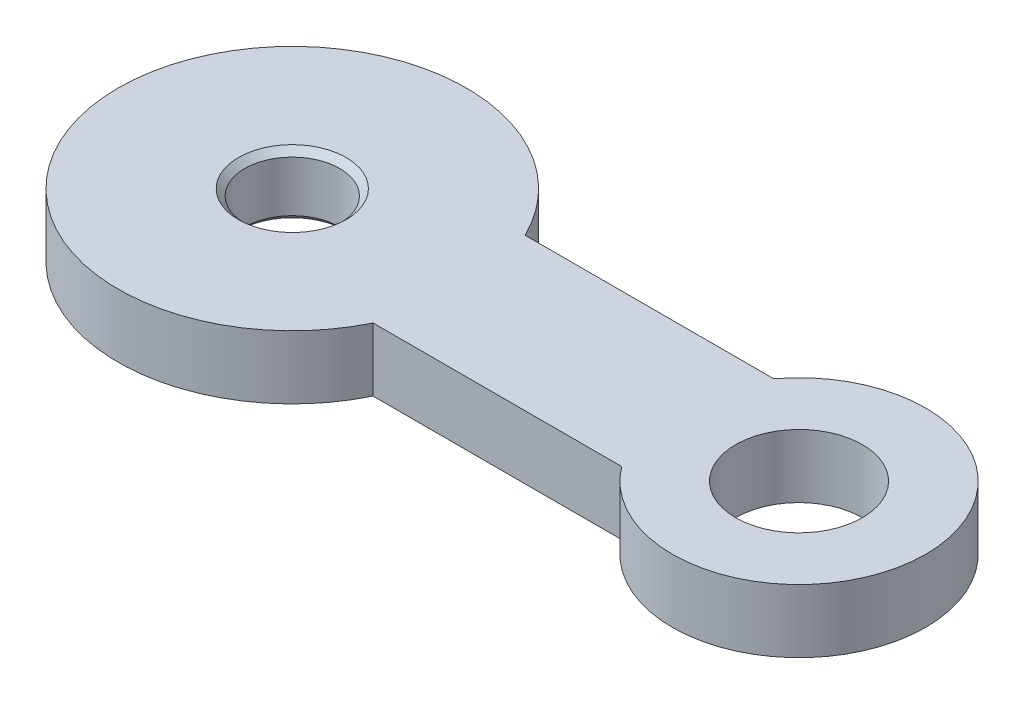
SolidWorks part; units mm, degrees
material "Brass"
ref_plane "Front Plane" through (0, 0, 0) normal (0, 0, 1) x (1, 0, 0)
ref_plane "Top Plane" through (0, 0, 0) normal (0, 1, 0) x (1, 0, 0)
ref_plane "Right Plane" through (0, 0, 0) normal (1, 0, 0) x (0, 0, -1)
sketch "Sketch1" plane through (0, 0, 0) normal (0, 1, 0) x (1, 0, 0)
  line L0 (31.4245, 15.24) -> (81.28, 15.24)
  line L1 (81.28, -15.24) -> (31.4245, -15.24)
  line L2 (0, 0) -> (101.6, 0) construction
  circle A0 centre (0, 0) radius 9.525
  arc A1 (31.4245, 15.24) -> (31.4245, -15.24) centre (0, 0) ccw
  circle A2 centre (101.6, 0) radius 12.7
  arc A3 (81.28, -15.24) -> (81.28, 15.24) centre (101.6, 0) ccw
  dimension "D1" = 25.4
  dimension "D2" = 19.05
  dimension "D3" = 25.4
  dimension "D4" = 50.8
  dimension "D5" = 15.24
  dimension "D6" = 15.24
  dimension "D7" = 101.6
extrude "Boss-Extrude1" add sketch "Sketch1" along normal blind 12.7
chamfer "Chamfer1" distance 1.27 angle 45 2 edges at (0, 0, 9.525) (0, 12.7, 9.525)
